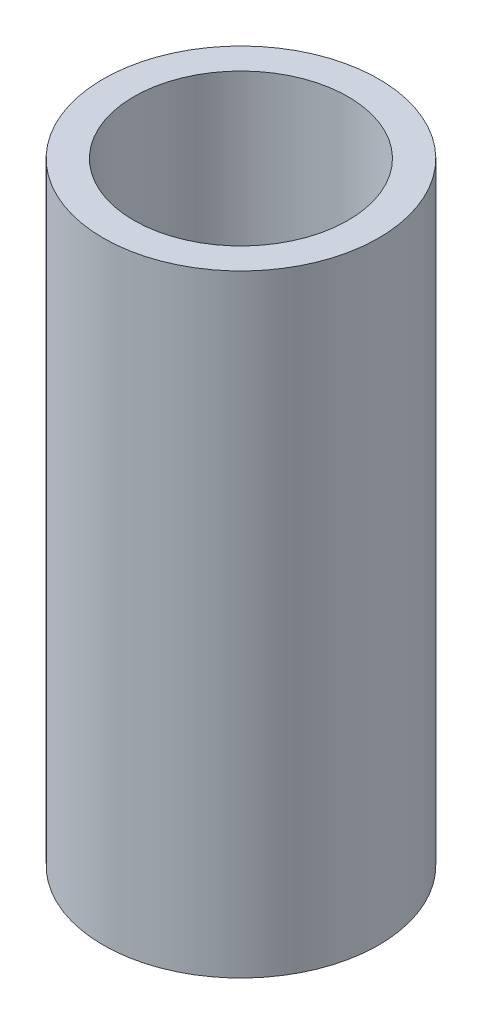
SolidWorks part; units mm, degrees
ref_plane "Front" through (0, 0, 0) normal (0, 0, 1) x (1, 0, 0)
ref_plane "Top" through (0, 0, 0) normal (0, 1, 0) x (1, 0, 0)
ref_plane "Right" through (0, 0, 0) normal (1, 0, 0) x (0, 0, -1)
sketch "Esboço1" plane through (0, 0, 0) normal (0, 1, 0) x (1, 0, 0)
  circle A0 centre (0, 0) radius 4.5
  circle A1 centre (0, 0) radius 3.5
  dimension "D1" = 9
  dimension "D2" = 7
extrude "Ressalto-extrusão1" add sketch "Esboço1" along normal blind 20
